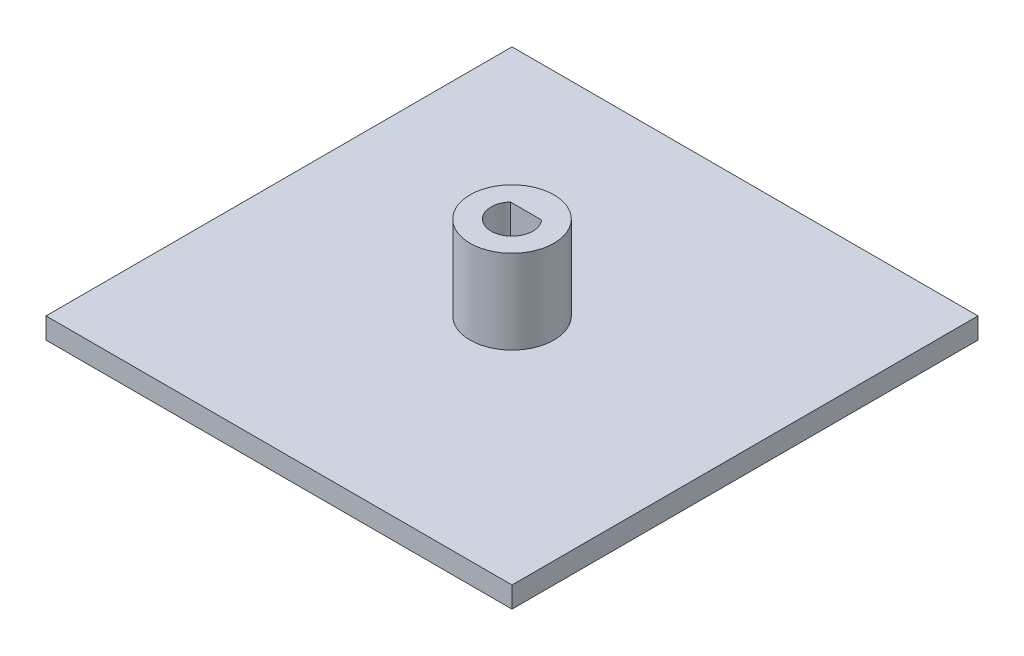
SolidWorks part; units mm, degrees
ref_plane "前视基准面" through (0, 0, 0) normal (0, 0, 1) x (1, 0, 0)
ref_plane "上视基准面" through (0, 0, 0) normal (0, 1, 0) x (1, 0, 0)
ref_plane "右视基准面" through (0, 0, 0) normal (1, 0, 0) x (0, 0, -1)
sketch "草图1" plane through (0, 0, 0) normal (0, 1, 0) x (1, 0, 0)
  line L1 (-16.6667, 16.6667) -> (16.6667, 16.6667)
  line L2 (-16.6667, 16.6667) -> (-16.6667, -16.6667)
  line L3 (-16.6667, -16.6667) -> (16.6667, -16.6667)
  line L4 (16.6667, 16.6667) -> (16.6667, -16.6667)
  line L5 (-16.6667, 16.6667) -> (16.6667, -16.6667) construction
  line L6 (-16.6667, -16.6667) -> (16.6667, 16.6667) construction
  point P0 (0, 0)
  dimension "D1" = 33.3333
  dimension "D2" = 33.3333
extrude "凸台-拉伸1" add sketch "草图1" along normal blind 1.5
ref_plane "基准面1" through (0, 1.5, 0) normal (0, 1, 0) x (1, 0, 0)
sketch "草图2" plane through (0, 1.5, 0) normal (0, 1, 0) x (1, 0, 0)
  circle A0 centre (0, 0) radius 3
  dimension "D1" = 6
extrude "凸台-拉伸2" add sketch "草图2" along normal blind 6
ref_plane "基准面2" through (0, 7.5, 0) normal (0, 1, 0) x (1, 0, 0)
sketch "草图3" plane through (0, 7.5, 0) normal (0, 1, 0) x (1, 0, 0)
  line L0 (-1.118, 1) -> (1.118, 1)
  arc A0 (-1.118, 1) -> (1.118, 1) centre (0, 0) ccw
  point P5 (0, 1)
  dimension "D1" = 3
  dimension "D2" = 1
extrude "切除-拉伸1" cut sketch "草图3" against normal blind 6
